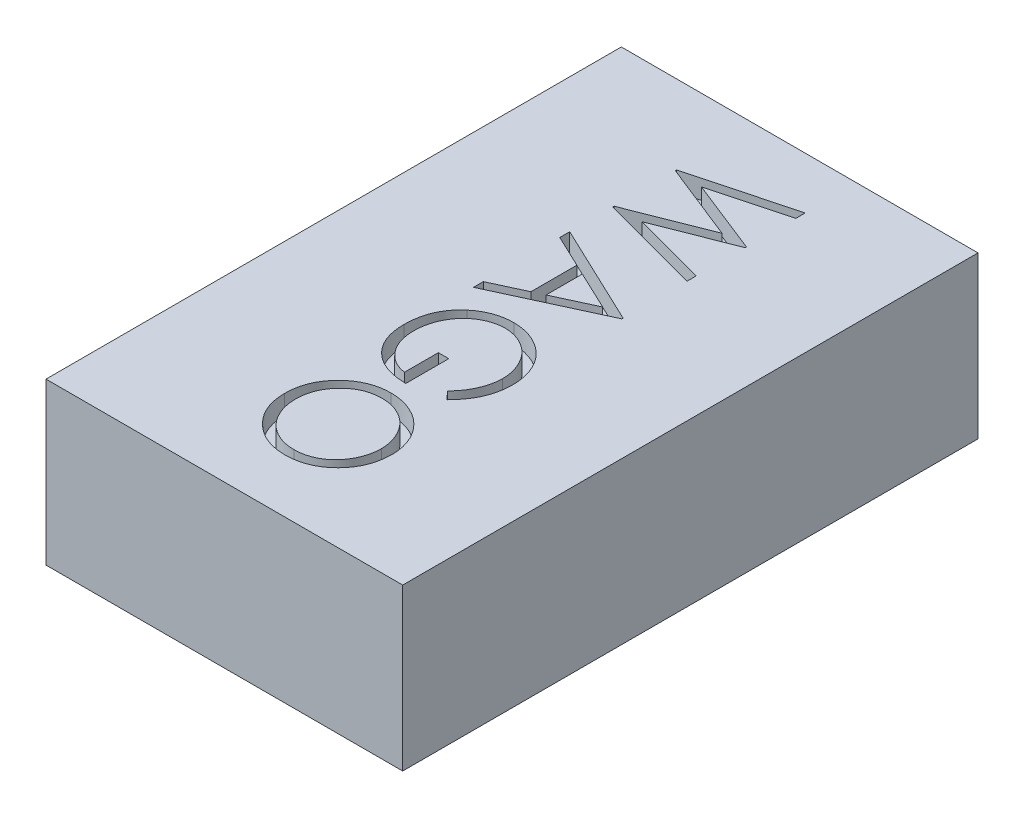
SolidWorks part; units mm, degrees
ref_plane "Front Plane" through (0, 0, 0) normal (0, 0, 1) x (1, 0, 0)
ref_plane "Top Plane" through (0, 0, 0) normal (0, 1, 0) x (1, 0, 0)
ref_plane "Right Plane" through (0, 0, 0) normal (1, 0, 0) x (0, 0, -1)
sketch "Sketch1" plane through (0, 0, 0) normal (0, 1, 0) x (1, 0, 0)
  line L1 (-9.3, 15) -> (9.3, 15)
  line L2 (-9.3, 15) -> (-9.3, -15)
  line L3 (-9.3, -15) -> (9.3, -15)
  line L4 (9.3, 15) -> (9.3, -15)
  line L5 (-9.3, 15) -> (9.3, -15) construction
  line L6 (-9.3, -15) -> (9.3, 15) construction
  point P0 (0, 0)
  dimension "D1" = 30
  dimension "D2" = 18.6
extrude "Boss-Extrude1" add sketch "Sketch1" along normal blind 8.4
sketch "Sketch2" plane through (0, 8.4, 0) normal (0, 1, 0) x (1, 0, 0)
  line L0 (-2.3, 12.6371) -> (-2.3, -10.6165) construction
  line L1 (-9.3, 15) -> (-9.3, -15) construction
  text T0 "WAGO" font "Century Gothic" height in points 20
  dimension "D1" = 7
extrude "Cut-Extrude1" cut sketch "Sketch2" against normal blind 1
